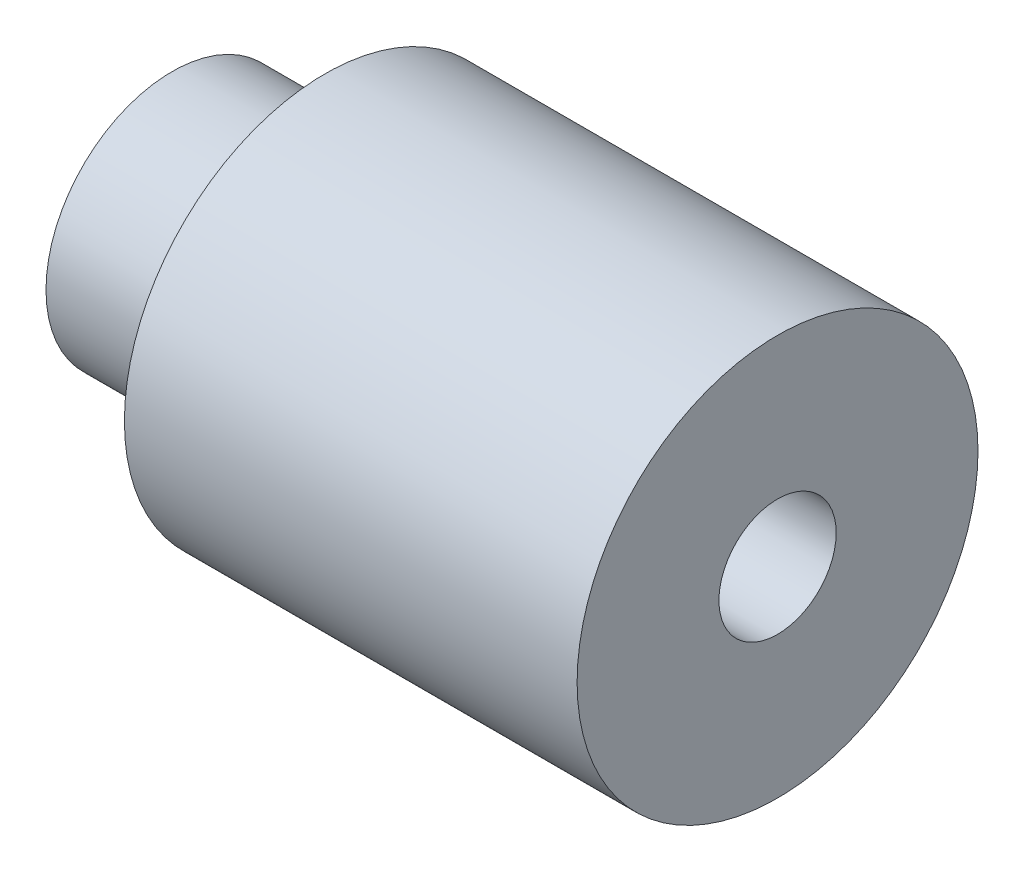
SolidWorks part; units mm, degrees
ref_plane "Front Plane" through (0, 0, 0) normal (0, 0, 1) x (1, 0, 0)
ref_plane "Top Plane" through (0, 0, 0) normal (0, 1, 0) x (1, 0, 0)
ref_plane "Right Plane" through (0, 0, 0) normal (1, 0, 0) x (0, 0, -1)
sketch "Sketch1" plane through (0, 0, 0) normal (1, 0, 0) x (0, 0, -1)
  circle A0 centre (0, 0) radius 2.15
  circle A1 centre (0, 0) radius 4.625
  dimension "D1" = 4.3
  dimension "D2" = 9.25
extrude "Boss-Extrude1" add sketch "Sketch1" along normal blind 5.6
sketch "Sketch2" plane through (5.6, 0, 0) normal (1, 0, 0) x (0, 0, -1)
  circle A0 centre (0, 0) radius 7.35
  circle A1 centre (0, 0) radius 2.15
  dimension "D1" = 14.7
extrude "Boss-Extrude2" add sketch "Sketch2" along normal blind 16.6 contours A0
